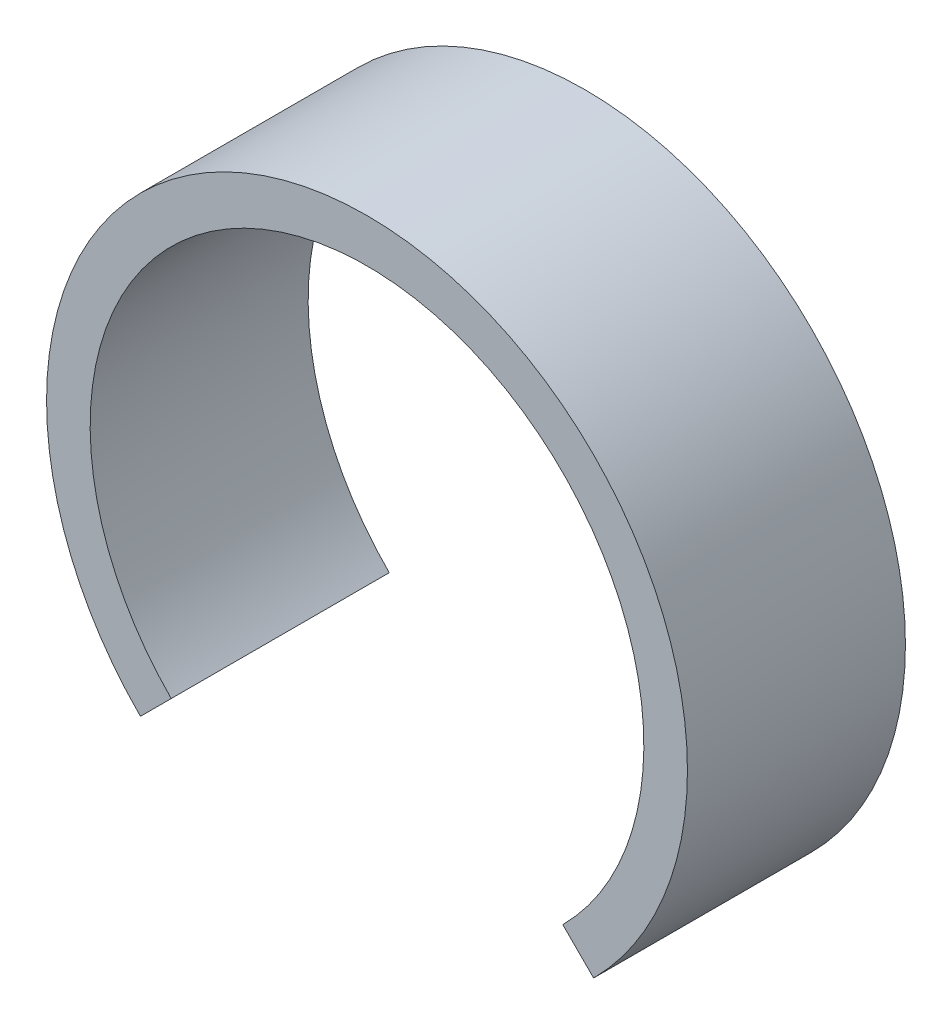
SolidWorks part; units mm, degrees
ref_plane "정면" through (0, 0, 0) normal (0, 0, 1) x (1, 0, 0)
ref_plane "윗면" through (0, 0, 0) normal (0, 1, 0) x (1, 0, 0)
ref_plane "우측면" through (0, 0, 0) normal (1, 0, 0) x (0, 0, -1)
sketch "스케치1" plane through (0, 0, 0) normal (0, 0, 1) x (1, 0, 0)
  line L0 (0, 0) -> (-10.3945, -10.3945)
  line L1 (0, 0) -> (0, -14.7) construction
  line L2 (0, 0) -> (10.3945, -10.3945)
  circle A0 centre (0, 0) radius 12.7
  circle A1 centre (0, 0) radius 14.7
  dimension "D1" = 25.4
  dimension "D3" = 45
  dimension "D4" = 45
  dimension "D2" = 2
extrude "보스-돌출1" add sketch "스케치1" along normal blind 10 contours L2 A1 L0 A0
